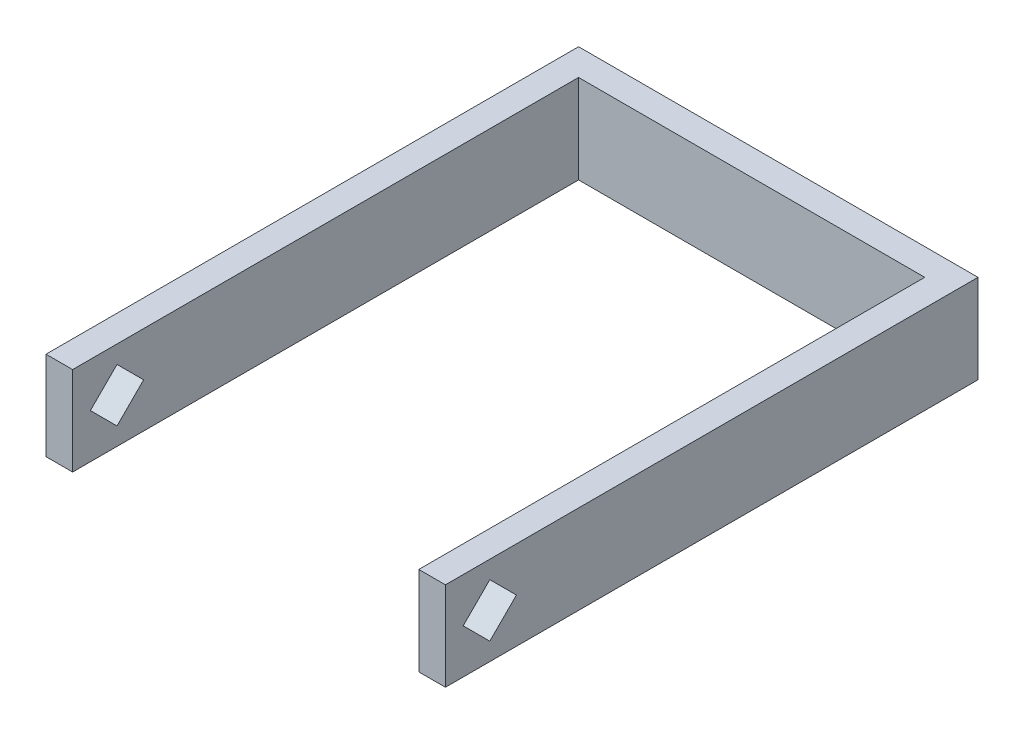
SolidWorks part; units mm, degrees
ref_plane "Front Plane" through (0, 0, 0) normal (0, 0, 1) x (1, 0, 0)
ref_plane "Top Plane" through (0, 0, 0) normal (0, 1, 0) x (1, 0, 0)
ref_plane "Right Plane" through (0, 0, 0) normal (1, 0, 0) x (0, 0, -1)
sketch "Sketch1" plane through (0, 0, 0) normal (0, 1, 0) x (1, 0, 0)
  line L0 (0, 19.5) -> (0, 22.5) construction
  line L1 (-19.5, -19.5) -> (19.5, -19.5) construction
  line L2 (-19.5, -19.5) -> (-19.5, 19.5)
  line L3 (-19.5, 19.5) -> (19.5, 19.5)
  line L4 (19.5, -19.5) -> (19.5, 19.5)
  line L5 (-19.5, -19.5) -> (19.5, 19.5) construction
  line L6 (-19.5, 19.5) -> (19.5, -19.5) construction
  line L7 (-22.5, -22.5) -> (-19.5, -22.5)
  line L8 (-22.5, -22.5) -> (-22.5, 22.5)
  line L9 (-22.5, 22.5) -> (22.5, 22.5)
  line L10 (22.5, -22.5) -> (22.5, 22.5)
  line L11 (-22.5, -22.5) -> (22.5, 22.5) construction
  line L12 (-22.5, 22.5) -> (22.5, -22.5) construction
  line L14 (19.5, -22.5) -> (22.5, -22.5)
  line L15 (19.5, -22.5) -> (19.5, -37.5)
  line L16 (-19.5, -19.5) -> (-19.5, -22.5)
  line L17 (19.5, -19.5) -> (19.5, -22.5)
  line L18 (19.5, -22.5) -> (22.5, -22.5)
  line L19 (19.5, -37.5) -> (22.5, -37.5)
  line L20 (22.5, -22.5) -> (22.5, -37.5)
  line L21 (-22.5, -22.5) -> (-19.5, -22.5)
  line L22 (-22.5, -22.5) -> (-22.5, -37.5)
  line L23 (-22.5, -37.5) -> (-19.5, -37.5)
  line L24 (-19.5, -22.5) -> (-19.5, -37.5)
  point P0 (0, 0)
  point P6 (0, 0)
  dimension "D1" = 3
  dimension "D2" = 39
  dimension "D3" = 15
extrude "Boss-Extrude1" add sketch "Sketch1" along normal blind 10 contours L4 L17 L14 L10 L9 L8 L7 L16 L2 L3 | L24 L7 L22 L23 | L20 L14 L15 L19
sketch "Sketch3" plane through (22.5, 0, 0) normal (1, 0, 0) x (0, 0, -1)
  line L0 (-32.5, 8) -> (-35.5, 5)
  line L1 (-32.5, 8) -> (-29.5, 5)
  line L2 (-35.5, 5) -> (-32.5, 2)
  line L3 (-29.5, 5) -> (-32.5, 2)
  line L4 (-32.5, 8) -> (-32.5, 2) construction
  line L5 (-35.5, 5) -> (-29.5, 5) construction
  line L6 (-37.5, 10) -> (-37.5, 0) construction
  line L7 (-32.5, 2) -> (-32.5, 0) construction
  line L8 (-37.5, 0) -> (22.5, 0) construction
  line L9 (-32.5, 8) -> (-32.5, 10) construction
  line L10 (-37.5, 10) -> (22.5, 10) construction
  line L11 (-35.5, 5) -> (-37.5, 5) construction
  point P1 (-32.5, 5)
  dimension "D1" = 2
extrude "Cut-Extrude1" cut sketch "Sketch3" against normal through all
